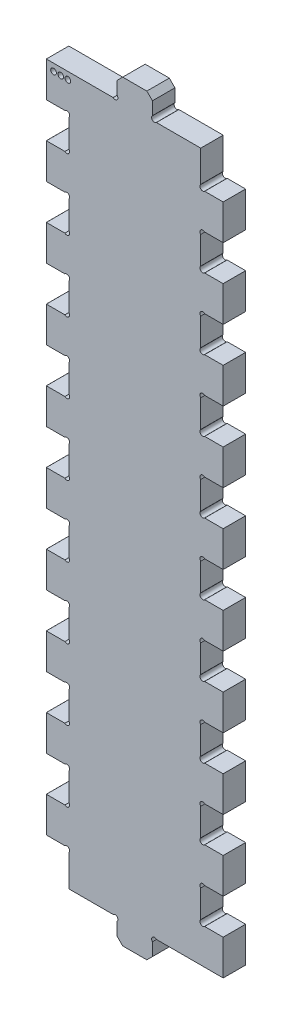
SolidWorks part; units mm, degrees
material "PVC Rigid"
ref_plane "Front Plane" through (0, 0, 0) normal (0, 0, 1) x (1, 0, 0)
ref_plane "Top Plane" through (0, 0, 0) normal (0, 1, 0) x (1, 0, 0)
ref_plane "Right Plane" through (0, 0, 0) normal (1, 0, 0) x (0, 0, -1)
sketch "Model" [suppressed]
  dimension "D3" = 0.7937
  dimension "D1" = 10
  dimension "D2" = 10
sketch "Sketch1" plane through (0, 0, 0) normal (0, 0, 1) x (1, 0, 0)
  line L1 (0, 0) -> (50, 0)
  line L2 (0, 0) -> (0, 200.0001)
  line L3 (0, 200.0001) -> (50, 200.0001)
  line L4 (50, 0) -> (50, 200.0001)
  dimension "D1" = 200.0001
  dimension "D2" = 50
extrude "Boss-Extrude1" add sketch "Sketch1" along normal blind 6.35
sketch "Sketch2" plane through (0, 0, 0) normal (0, 0, 1) x (1, 0, 0)
  line L0 (0, 100.0001) -> (50, 100.0001) construction
  line L1 (50, 200.0001) -> (0, 200.0001) construction
  line L2 (25, 200.0001) -> (25, 203.1751) construction
  line L3 (20, 206.3501) -> (30, 206.3501)
  line L4 (20, 206.3501) -> (20, 200.0001)
  line L5 (20, 200.0001) -> (30, 200.0001)
  line L6 (30, 206.3501) -> (30, 200.0001)
  line L7 (20, 206.3501) -> (30, 200.0001) construction
  line L8 (20, 200.0001) -> (30, 206.3501) construction
  line L9 (0, 200.0001) -> (0, 0) construction
  line L10 (50, 0) -> (50, 200.0001) construction
  line L11 (20, 0) -> (30, -6.35) construction
  line L12 (20, -6.35) -> (30, 0) construction
  line L13 (25, 0) -> (25, -3.175) construction
  line L14 (30, -6.35) -> (30, 0)
  line L15 (20, 0) -> (30, 0)
  line L16 (20, -6.35) -> (20, 0)
  line L17 (20, -6.35) -> (30, -6.35)
  dimension "D1" = 6.35
  dimension "D2" = 10
extrude "Boss-Extrude2" add sketch "Sketch2" along normal blind 6.35
sketch "Sketch3" plane through (0, 0, 6.35) normal (0, 0, 1) x (1, 0, 0)
  line L0 (25, 206.3501) -> (25, -6.35) construction
  line L1 (30, 206.3501) -> (20, 206.3501) construction
  line L2 (20, -6.35) -> (30, -6.35) construction
  line L3 (6.35, 200.0001) -> (6.35, 0) construction
  line L4 (20, 200.0001) -> (0, 200.0001) construction
  line L5 (0, 0) -> (20, 0) construction
  line L6 (0, 200.0001) -> (0, 0) construction
  line L7 (6.35, 0) -> (0, 0)
  line L8 (6.35, 0) -> (6.35, 10)
  line L9 (6.35, 10) -> (0, 10)
  line L10 (0, 0) -> (0, 10)
  line L11 (50, 0) -> (50, 10)
  line L12 (43.65, 10) -> (50, 10)
  line L13 (43.65, 0) -> (43.65, 10)
  line L14 (43.65, 0) -> (50, 0)
  dimension "D1" = 6.35
  dimension "D2" = 10
extrude "Cut-Extrude1" [suppressed] cut sketch "Sketch3" against normal blind 6.35
pattern_linear "LPattern2" [suppressed] count 10 spacing 20
sketch "Sketch4" [suppressed] plane through (0, 0, 6.35) normal (0, 0, 1) x (1, 0, 0)
  line L0 (0, 10) -> (6.35, 0) construction
  line L1 (6.35, 10) -> (5.2275, 10) construction
  line L2 (0.5613, 0.5613) -> (5.7887, 0.5613) construction
  line L3 (0.5613, 0.5613) -> (0.5613, 9.4387) construction
  line L4 (0.5613, 9.4387) -> (5.7887, 9.4387) construction
  line L5 (5.7887, 0.5613) -> (5.7887, 9.4387) construction
  line L6 (0.5613, 0.5613) -> (5.7887, 9.4387) construction
  line L7 (0.5613, 9.4387) -> (5.7887, 0.5613) construction
  line L8 (6.35, 10) -> (0, 10) construction
  line L9 (6.35, 10) -> (6.35, 8.8775) construction
  line L10 (6.35, 0) -> (6.35, 10) construction
  line L11 (25, 206.3501) -> (25, -6.35) construction
  line L12 (30, 206.3501) -> (20, 206.3501) construction
  line L13 (20, -6.35) -> (30, -6.35) construction
  line L14 (44.2113, 9.4387) -> (44.2113, 20.5613) construction
  line L15 (43.65, 10) -> (43.65, 8.8775) construction
  line L16 (49.4387, 9.4387) -> (44.2113, 0.5613) construction
  line L17 (49.4387, 0.5613) -> (44.2113, 9.4387) construction
  line L18 (44.2113, 0.5613) -> (44.2113, 9.4387) construction
  line L19 (49.4387, 9.4387) -> (44.2113, 9.4387) construction
  line L20 (49.4387, 0.5613) -> (49.4387, 9.4387) construction
  line L21 (49.4387, 0.5613) -> (44.2113, 0.5613) construction
  line L22 (43.65, 10) -> (44.7725, 10) construction
  line L23 (5.7887, 9.4387) -> (5.7887, 20.5613) construction
  line L24 (50, 10) -> (43.65, 0) construction
  circle A0 centre (5.7887, 9.4387) radius 0.7938
  circle A4 centre (5.7887, 20.5613) radius 0.7938
  circle A7 centre (44.2113, 20.5613) radius 0.7937
  circle A8 centre (44.2113, 9.4387) radius 0.7937
  point P4 (3.175, 5)
  point P40 (46.825, 5)
  dimension "D1" = 1.5875
extrude "Cut-Extrude3" [suppressed] cut sketch "Sketch4" against normal blind 6.35
pattern_linear "LPattern3" [suppressed] count 9 spacing 20
sketch "Sketch8" plane through (0, 0, 6.35) normal (0, 0, 1) x (1, 0, 0)
  line L0 (6.35, 200.0001) -> (6.35, 0) construction
  line L1 (20, 200.0001) -> (0, 200.0001) construction
  line L2 (0, 0) -> (20, 0) construction
  line L3 (0, 200.0001) -> (0, 0) construction
  line L4 (43.65, 200.0001) -> (43.65, 0) construction
  line L5 (0, 0) -> (6.35, 0)
  line L6 (0, 0) -> (0, 10)
  line L7 (0, 10) -> (6.35, 10)
  line L8 (6.35, 0) -> (6.35, 10)
  line L9 (50, 200.0001) -> (30, 200.0001) construction
  line L10 (30, 0) -> (50, 0) construction
  line L11 (50, 0) -> (50, 200.0001) construction
  line L12 (43.65, 10) -> (50, 10)
  line L13 (43.65, 10) -> (43.65, 20)
  line L14 (43.65, 20) -> (50, 20)
  line L15 (50, 10) -> (50, 20)
  dimension "D1" = 6.35
  dimension "D2" = 10
  dimension "D3" = 10
  dimension "D4" = 6.35
  dimension "D5" = 10
extrude "Cut-Extrude6" cut sketch "Sketch8" against normal through all
pattern_linear "LPattern4" count 10 spacing 20 along (0, 1, 0) of "Cut-Extrude6"
sketch "Sketch9" plane through (0, 0, 6.35) normal (0, 0, 1) x (1, 0, 0)
  line L0 (0, 30) -> (6.35, 20) construction
  line L1 (6.35, 30) -> (5.2275, 30) construction
  line L2 (0.5613, 20.5613) -> (5.7887, 20.5613) construction
  line L3 (0.5613, 20.5613) -> (0.5613, 29.4388) construction
  line L4 (0.5613, 29.4388) -> (5.7887, 29.4388) construction
  line L5 (5.7887, 20.5613) -> (5.7887, 29.4388) construction
  line L6 (0.5613, 20.5613) -> (5.7887, 29.4388) construction
  line L7 (0.5613, 29.4388) -> (5.7887, 20.5613) construction
  line L8 (6.35, 30) -> (0, 30) construction
  line L9 (6.35, 30) -> (6.35, 28.8775) construction
  line L10 (6.35, 20) -> (6.35, 30) construction
  line L11 (43.65, 20) -> (50, 10) construction
  line L12 (43.65, 20) -> (44.7725, 20) construction
  line L13 (44.2113, 10.5613) -> (49.4387, 10.5613) construction
  line L14 (44.2113, 10.5613) -> (44.2113, 19.4387) construction
  line L15 (44.2113, 19.4387) -> (49.4387, 19.4387) construction
  line L16 (49.4387, 10.5613) -> (49.4387, 19.4387) construction
  line L17 (44.2113, 10.5613) -> (49.4387, 19.4387) construction
  line L18 (44.2113, 19.4387) -> (49.4387, 10.5613) construction
  line L19 (50, 20) -> (43.65, 20) construction
  line L20 (43.65, 20) -> (43.65, 18.8775) construction
  line L21 (43.65, 20) -> (43.65, 10) construction
  line L22 (50, 20) -> (50, 30) construction
  circle A0 centre (5.7887, 29.4388) radius 0.7938
  circle A1 centre (5.7887, 20.5613) radius 0.7938
  circle A2 centre (44.2113, 19.4387) radius 0.7937
  circle A3 centre (44.2113, 10.5613) radius 0.7937
  point P4 (3.175, 25)
  point P23 (46.825, 15)
  dimension "D1" = 1.5875
  dimension "D2" = 10
extrude "Cut-Extrude7" cut sketch "Sketch9" against normal through all
pattern_linear "LPattern5" count 9 spacing 20 along (0, 1, 0) of "Cut-Extrude7"
sketch "Sketch10" plane through (0, 0, 6.35) normal (0, 0, 1) x (1, 0, 0)
  line L0 (0, 10) -> (6.35, 0) construction
  line L1 (5.2275, 10) -> (6.35, 10) construction
  line L2 (0.5613, 0.5613) -> (5.7887, 0.5613) construction
  line L3 (0.5613, 0.5613) -> (0.5613, 9.4387) construction
  line L4 (0.5613, 9.4387) -> (5.7887, 9.4387) construction
  line L5 (5.7887, 0.5613) -> (5.7887, 9.4387) construction
  line L6 (0.5613, 0.5613) -> (5.7887, 9.4387) construction
  line L7 (0.5613, 9.4387) -> (5.7887, 0.5613) construction
  line L8 (6.35, 10) -> (0, 10) construction
  line L9 (6.35, 10) -> (6.35, 8.8775) construction
  line L10 (6.35, 0) -> (6.35, 10) construction
  line L11 (6.35, 5) -> (3.175, 5) construction
  line L12 (0, 200.0001) -> (50, 0) construction
  line L13 (43.65, 200.0001) -> (50, 190.0001) construction
  line L14 (44.7725, 190.0001) -> (43.65, 190.0001) construction
  line L15 (44.2113, 190.5614) -> (49.4387, 190.5614) construction
  line L16 (44.2113, 190.5614) -> (44.2113, 199.4388) construction
  line L17 (44.2113, 199.4388) -> (49.4387, 199.4388) construction
  line L18 (49.4387, 190.5614) -> (49.4387, 199.4388) construction
  line L19 (44.2113, 190.5614) -> (49.4387, 199.4388) construction
  line L20 (44.2113, 199.4388) -> (49.4387, 190.5614) construction
  line L21 (43.65, 190.0001) -> (50, 190.0001) construction
  line L22 (43.65, 190.0001) -> (43.65, 191.1226) construction
  line L23 (43.65, 200.0001) -> (43.65, 190.0001) construction
  circle A0 centre (5.7887, 9.4387) radius 0.7938
  circle A2 centre (44.2113, 190.5614) radius 0.7937
  point P4 (3.175, 5)
  point P28 (46.825, 195.0001)
  dimension "D1" = 1.5875
  dimension "D2" = 1.5875
extrude "Cut-Extrude8" cut sketch "Sketch10" against normal through all
chamfer "Chamfer1" distance 1.5875 angle 45 4 edges at (30, -6.35, 3.175) (20, -6.35, 3.175) (20, 206.3501, 3.175) (30, 206.3501, 3.175)
sketch "Sketch5" [suppressed] plane through (0, 0, 6.35) normal (0, 0, 1) x (1, 0, 0)
  line L0 (6.35, 180.0001) -> (0, 190.0001) construction
  line L1 (6.35, 190.0001) -> (5.2275, 190.0001) construction
  line L2 (0.5613, 180.5614) -> (5.7887, 180.5614) construction
  line L3 (0.5613, 180.5614) -> (0.5613, 189.4388) construction
  line L4 (0.5613, 189.4388) -> (5.7887, 189.4388) construction
  line L5 (5.7887, 180.5614) -> (5.7887, 189.4388) construction
  line L6 (0.5613, 180.5614) -> (5.7887, 189.4388) construction
  line L7 (0.5613, 189.4388) -> (5.7887, 180.5614) construction
  line L8 (6.35, 190.0001) -> (0, 190.0001) construction
  line L9 (6.35, 190.0001) -> (6.35, 188.8776) construction
  line L10 (6.35, 181.1226) -> (6.35, 190.0001) construction
  line L15 (25, 206.3501) -> (25, -6.35) construction
  line L16 (28.4125, 206.3501) -> (21.5875, 206.3501) construction
  line L17 (21.5875, -6.35) -> (28.4125, -6.35) construction
  line L20 (43.65, 190.0001) -> (43.65, 188.8776) construction
  line L21 (49.4387, 189.4388) -> (44.2113, 180.5614) construction
  line L22 (49.4387, 180.5614) -> (44.2113, 189.4388) construction
  line L23 (44.2113, 180.5614) -> (44.2113, 189.4388) construction
  line L24 (49.4387, 189.4388) -> (44.2113, 189.4388) construction
  line L25 (49.4387, 180.5614) -> (49.4387, 189.4388) construction
  line L26 (49.4387, 180.5614) -> (44.2113, 180.5614) construction
  line L27 (43.65, 190.0001) -> (44.7725, 190.0001) construction
  line L28 (43.65, 180.0001) -> (50, 190.0001) construction
  line L29 (50, 100.0001) -> (0, 100.0001) construction
  arc A0 (5.2275, 180.0001) -> (6.35, 181.1226) centre (5.7887, 180.5614) ccw construction
  circle A1 centre (5.7887, 189.4388) radius 0.7938
  circle A4 centre (44.2113, 189.4388) radius 0.7937
  point P6 (3.175, 185.0001)
  point P51 (46.825, 185.0001)
  point P56 (25, 100.0001)
  dimension "D1" = 1.5875
extrude "Cut-Extrude4" [suppressed] cut sketch "Sketch5" against normal blind 6.35
sketch "Sketch11" plane through (0, 0, 0) normal (0, 0, 1) x (1, 0, 0)
  line L0 (28.4125, 206.3501) -> (21.5875, 206.3501) construction
  line L11 (20, 201.1226) -> (20, 200.0001) construction
  line L13 (20, 200.0001) -> (18.8775, 200.0001) construction
  line L15 (25, 206.3501) -> (25, -6.35) construction
  line L18 (30, 200.0001) -> (31.1225, 200.0001) construction
  line L19 (30, 201.1226) -> (30, 200.0001) construction
  line L29 (50, 100.0001) -> (0, 100.0001) construction
  circle A2 centre (19.4387, 200.5614) radius 0.7937
  circle A3 centre (30.5613, 200.5614) radius 0.7937
  circle A5 centre (19.4387, -0.5613) radius 0.7937
  circle A6 centre (30.5613, -0.5613) radius 0.7937
  point P56 (25, 100.0001)
  dimension "D1" = 1.5875
  dimension "D2" = 19.4387
  dimension "D3" = 100.0001
  dimension "D4" = 200.0001
extrude "Cut-Extrude10" cut sketch "Sketch11" along normal through all
sketch "Sketch6" [suppressed] plane through (0, 0, 6.35) normal (0, 0, 1) x (1, 0, 0)
  line L0 (6.604, 2.032) -> (43.65, 2.032) construction
  line L1 (43.65, 10) -> (43.65, 0) construction
  line L2 (6.35, 0) -> (18.8775, 0) construction
  line L4 (0, 20) -> (0, 10) construction
  text T0 "COL_BIT" font "Consolas" height 3.5
  dimension "D1" = 2.032
  dimension "D2" = 6.604
extrude "Cut-Extrude5" [suppressed] cut sketch "Sketch6" against normal blind 2.54
sketch "Sketch12" plane through (0, 0, 6.35) normal (0, 0, 1) x (1, 0, 0)
  line L0 (6.604, 2.032) -> (40.0372, 2.032) construction
  text T0 "COL_BIT" font "Consolas" height 3.5
  dimension "D1" = 2.032
  dimension "D2" = 6.604
extrude "Cut-Extrude11" [suppressed] cut sketch "Sketch12" against normal blind 2.54
sketch "Sketch13" [suppressed] plane through (0, 0, 6.35) normal (0, 0, 1) x (1, 0, 0)
  line L0 (0, 10) -> (6.35, 0) construction
  line L1 (5.2275, 10) -> (0, 10) construction
  line L2 (6.337, -0.0127) -> (0.013, -0.0127)
  line L3 (6.337, -0.0127) -> (6.337, 10.0127)
  line L4 (6.337, 10.0127) -> (0.013, 10.0127)
  line L5 (0.013, -0.0127) -> (0.013, 10.0127)
  line L6 (6.337, -0.0127) -> (0.013, 10.0127) construction
  line L7 (6.337, 10.0127) -> (0.013, -0.0127) construction
  line L8 (25, 206.3501) -> (25, -6.35) construction
  line L9 (28.4125, 206.3501) -> (21.5875, 206.3501) construction
  line L10 (21.5875, -6.35) -> (28.4125, -6.35) construction
  line L11 (43.663, 10.0127) -> (49.987, -0.0127) construction
  line L12 (43.663, -0.0127) -> (49.987, 10.0127) construction
  line L13 (50, 10) -> (43.65, 0) construction
  line L14 (49.987, -0.0127) -> (49.987, 10.0127)
  line L15 (43.663, 10.0127) -> (49.987, 10.0127)
  line L16 (43.663, -0.0127) -> (43.663, 10.0127)
  line L17 (43.663, -0.0127) -> (49.987, -0.0127)
  arc A0 (6.35, 8.8775) -> (5.2275, 10) centre (5.7887, 9.4387) ccw construction
  point P4 (3.175, 5)
  point P26 (46.825, 5)
  dimension "D1" = 0.0127
extrude "Cut-Extrude12" [suppressed] cut sketch "Sketch13" against normal through all
pattern_linear "LPattern6" [suppressed] count 10 spacing 20
sketch "Sketch14" plane through (0, 0, 6.35) normal (0, 0, 1) x (1, 0, 0)
  line L0 (0, 10) -> (6.35, 0) construction
  line L1 (5.2275, 10) -> (0, 10) construction
  line L2 (0.013, -0.0127) -> (6.337, -0.0127)
  line L3 (0.013, -0.0127) -> (0.013, 10.0127)
  line L4 (0.013, 10.0127) -> (6.337, 10.0127)
  line L5 (6.337, -0.0127) -> (6.337, 10.0127)
  line L6 (0.013, -0.0127) -> (6.337, 10.0127) construction
  line L7 (0.013, 10.0127) -> (6.337, -0.0127) construction
  line L8 (43.65, 20) -> (50, 10) construction
  line L9 (50, 20) -> (44.7725, 20) construction
  line L10 (43.663, 9.9873) -> (49.987, 9.9873)
  line L11 (43.663, 9.9873) -> (43.663, 20.0127)
  line L12 (43.663, 20.0127) -> (49.987, 20.0127)
  line L13 (49.987, 9.9873) -> (49.987, 20.0127)
  line L14 (43.663, 9.9873) -> (49.987, 20.0127) construction
  line L15 (43.663, 20.0127) -> (49.987, 9.9873) construction
  arc A0 (6.35, 8.8775) -> (5.2275, 10) centre (5.7887, 9.4387) ccw construction
  arc A1 (44.7725, 20) -> (43.65, 18.8775) centre (44.2113, 19.4387) ccw construction
  point P4 (3.175, 5)
  point P9 (46.825, 15)
  dimension "D1" = 0.0127
  dimension "D2" = 0.0127
extrude "Cut-Extrude13" cut sketch "Sketch14" against normal through all
pattern_linear "LPattern7" count 10 spacing 20 along (0, 1, 0) of "Cut-Extrude13"
sketch "Sketch15" plane through (0, 0, 6.35) normal (0, 0, 1) x (1, 0, 0)
  line L1 (0, 200.0001) -> (2.032, 200.0001) construction
  line L2 (0, 200.0001) -> (0, 197.9681) construction
  line L3 (0, 197.9681) -> (2.032, 197.9681) construction
  line L4 (2.032, 200.0001) -> (2.032, 197.9681) construction
  circle A0 centre (2.032, 197.9681) radius 0.7938
  dimension "D2" = 1.5875
  dimension "D1" = 2.032
extrude "Cut-Extrude14" cut sketch "Sketch15" against normal blind 3.175
pattern_linear "LPattern8" count 3 spacing 2.032 along (1, 0, 0) of "Cut-Extrude14"
equation "\"tHeight\"=0.25"
equation "\"D1@Sketch2\"=\"tHeight\""
equation "\"tWidth\"=0.393701"
equation "\"D2@Sketch2\"=\"tWidth\""
equation "\"D1@Sketch1\"=\"tWidth\"*20"
equation "\"D1@Sketch3\"=\"tHeight\""
equation "\"D2@Sketch3\"=\"tWidth\""
equation "\"D3@LPattern2\"=\"tWidth\"*2"
equation "\"D3@LPattern3\"=\"tWidth\"*2"
equation "\"D1@Sketch8\"=\"tHeight\""
equation "\"D2@Sketch8\"=\"tWidth\""
equation "\"D3@Sketch8\"=\"tWidth\""
equation "\"D4@Sketch8\"=\"tHeight\""
equation "\"D5@Sketch8\"=\"tWidth\""
equation "\"D3@LPattern4\"=\"tWidth\"*2"
equation "\"D3@LPattern5\"=\"tWidth\"*2"
equation "\"D2@Sketch9\"=\"tWidth\""
equation "\"tol\"=0.0005"
equation "\"D1@Sketch13\"=\"tol\""
equation "\"D3@LPattern6\"=\"tWidth\"*2"
equation "\"D1@Sketch14\"=\"tol\""
equation "\"D2@Sketch14\"=\"tol\""
equation "\"version\"= 3"
equation "\"D1@LPattern8\"=\"version\""
